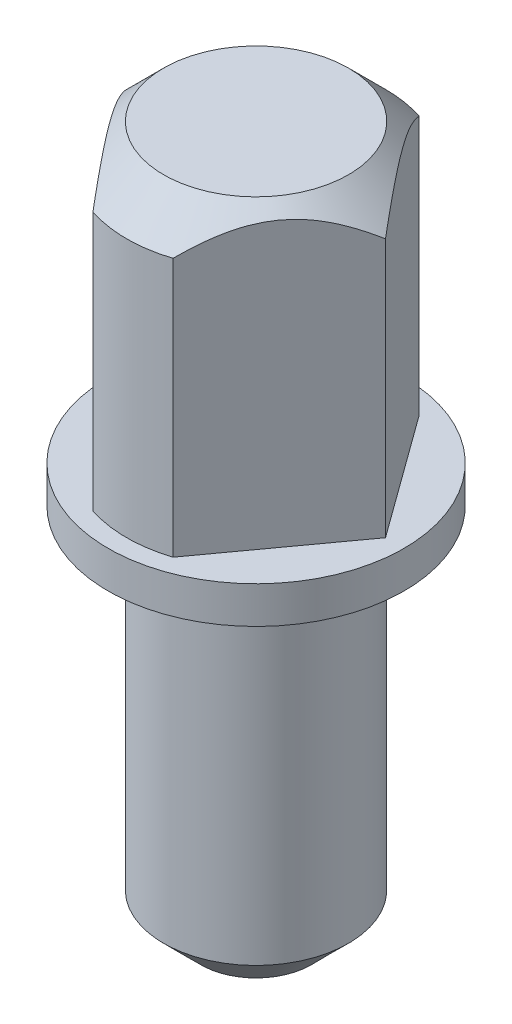
SolidWorks part; units mm, degrees
ref_plane "前视基准面" through (0, 0, 0) normal (0, 0, 1) x (1, 0, 0)
ref_plane "上视基准面" through (0, 0, 0) normal (0, 1, 0) x (1, 0, 0)
ref_plane "右视基准面" through (0, 0, 0) normal (1, 0, 0) x (0, 0, -1)
sketch "草图1" plane through (0, 0, 0) normal (0, 0, 1) x (1, 0, 0)
  line L0 (0, 0) -> (0, 19)
  line L1 (0, 19) -> (2.5, 19)
  line L2 (3.5, 18) -> (3.5, 11)
  line L3 (3.5, 11) -> (4, 11)
  line L4 (4, 11) -> (4, 10)
  line L5 (4, 10) -> (2.5, 10)
  line L6 (2.5, 10) -> (2.5, 1)
  line L7 (1.5, 0) -> (0, 0)
  line L8 (2.5, 19) -> (3.5, 18)
  line L9 (2.5, 1) -> (1.5, 0)
  point P3 (3.5, 19)
  point P9 (2.5, 0)
  dimension "D1" = 3.5
  dimension "D2" = 2.5
  dimension "D3" = 1
  dimension "D4" = 4
  dimension "D5" = 10
  dimension "D6" = 8
revolve "旋转1" add sketch "草图1" angle 360 about L0
sketch "草图2" plane through (0, 19, 0) normal (0, 1, 0) x (1, 0, 0)
  line L3 (0, 4.8208) -> (-3.5, 0)
  line L4 (0, 4.8208) -> (3.5, 0)
  line L5 (-3.5, 0) -> (0, -4.8208)
  line L6 (3.5, 0) -> (0, -4.8208)
  circle A2 centre (0, 0) radius 3.5 construction
  circle A3 centre (0, 0) radius 3.5 construction
  circle A4 centre (0, 0) radius 6.2827
extrude "切除-拉伸2" cut sketch "草图2" against normal up to surface (8 mm away) up to face at (0, 11, -3.5)
